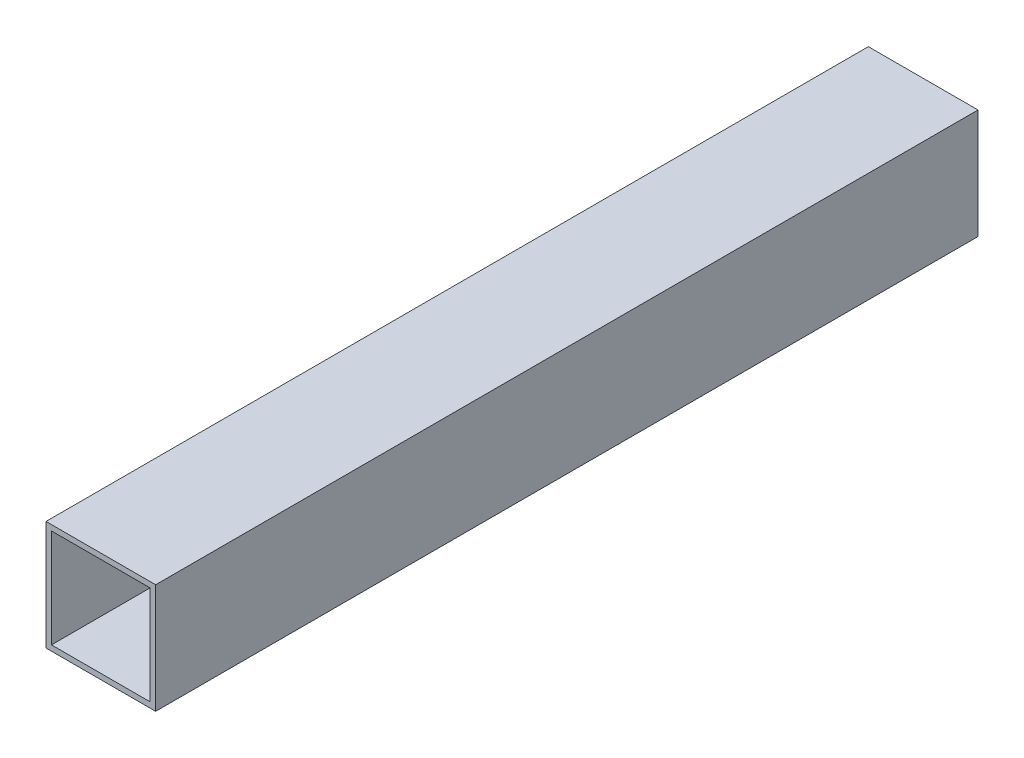
SolidWorks part; units mm, degrees
ref_plane "前视基准面" through (0, 0, 0) normal (0, 0, 1) x (1, 0, 0)
ref_plane "上视基准面" through (0, 0, 0) normal (0, 1, 0) x (1, 0, 0)
ref_plane "右视基准面" through (0, 0, 0) normal (1, 0, 0) x (0, 0, -1)
other "Configuration Table"
sketch "草图1" plane through (0, 0, 0) normal (0, 0, 1) x (1, 0, 0)
  line L0 (-6.5, 11.5) -> (11.5, 11.5)
  line L1 (-7.5, -7.5) -> (12.5, -7.5)
  line L2 (-7.5, -7.5) -> (-7.5, 12.5)
  line L3 (-7.5, 12.5) -> (12.5, 12.5)
  line L4 (12.5, -7.5) -> (12.5, 12.5)
  line L5 (11.5, -6.5) -> (11.5, 11.5)
  line L6 (-6.5, -6.5) -> (11.5, -6.5)
  line L7 (-6.5, -6.5) -> (-6.5, 11.5)
  point P0 (0, 0)
  dimension "D1" = 20
  dimension "D2" = 1
extrude "凸台-拉伸1" add sketch "草图1" along normal blind 150
